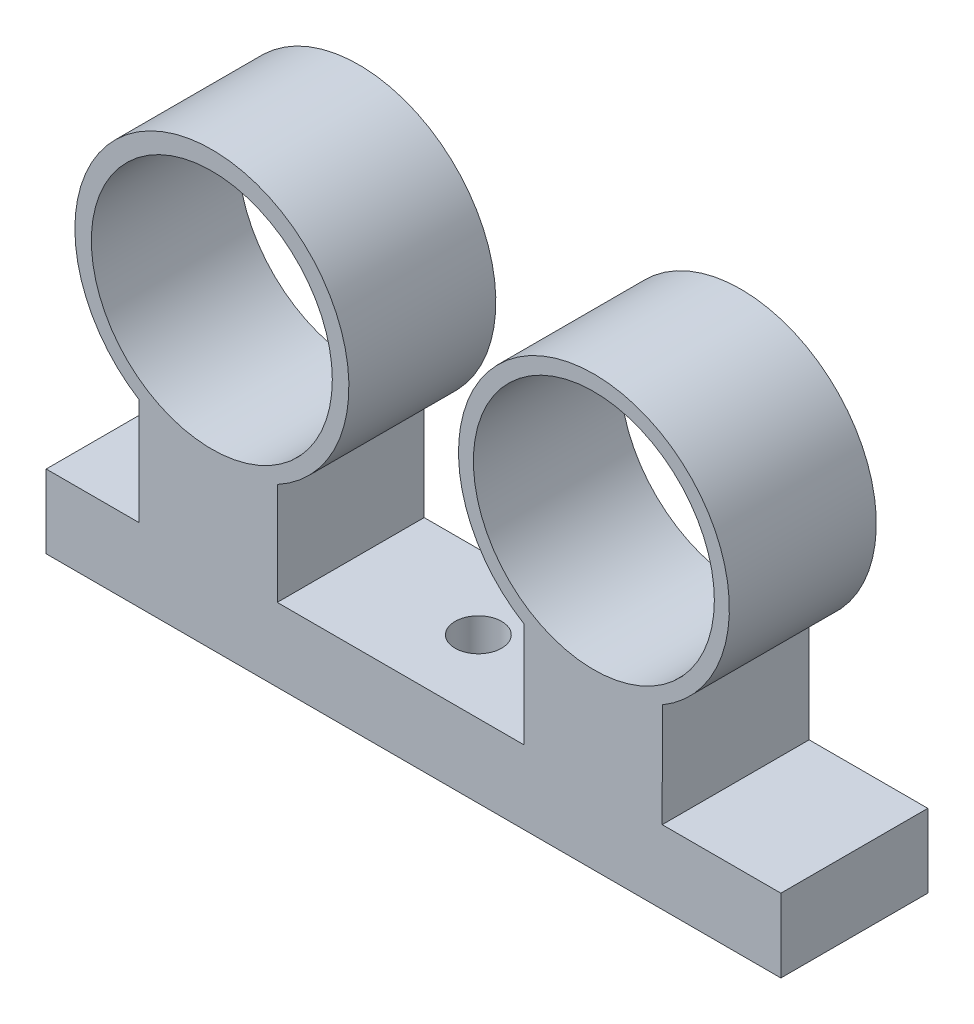
SolidWorks part; units mm, degrees
ref_plane "Alzado" through (0, 0, 0) normal (0, 0, 1) x (1, 0, 0)
ref_plane "Planta" through (0, 0, 0) normal (0, 1, 0) x (1, 0, 0)
ref_plane "Vista lateral" through (0, 0, 0) normal (1, 0, 0) x (0, 0, -1)
sketch "Sketch1" plane through (0, 0, 0) normal (0, 0, 1) x (1, 0, 0)
  line L0 (-4.1885, 12.6077) -> (-4.1885, 5.3678)
  line L1 (-10.5195, 0.3678) -> (39.4805, 0.3678)
  line L2 (-10.5195, 0.3678) -> (-10.5195, 5.3678)
  line L4 (39.4805, 0.3678) -> (39.4805, 5.3678)
  line L5 (-10.5195, 0.3678) -> (39.4805, 5.3678) construction
  line L6 (-10.5195, 5.3678) -> (39.4805, 0.3678) construction
  line L8 (5.2058, 5.3678) -> (5.2058, 12.317)
  line L9 (22.0109, 12.4897) -> (22.0055, 5.3678)
  line L11 (31.4055, 5.3678) -> (31.4109, 12.4339)
  line L12 (-10.5195, 5.3678) -> (-4.1885, 5.3678)
  line L13 (5.2058, 5.3678) -> (22.0055, 5.3678)
  line L14 (31.4055, 5.3678) -> (39.4805, 5.3678)
  circle A0 centre (26.7532, 20.3678) radius 8.2
  circle A1 centre (0.7532, 20.3678) radius 8.2
  arc A5 (-4.1885, 12.6077) -> (5.2058, 12.317) centre (0.7577, 20.5122) cw
  arc A6 (22.0109, 12.4897) -> (31.4109, 12.4339) centre (26.758, 20.391) cw
  point P4 (17.3377, 2.5)
  dimension "D3" = 16.4
  dimension "D5" = 16.4
  dimension "D4" = 9.4
  dimension "D1" = 5
  dimension "D2" = 50
  dimension "D6" = 26
extrude "Boss-Extrude1" add sketch "Sketch1" along normal blind 10
sketch "Sketch2" plane through (0, 5.3678, 0) normal (0, 1, 0) x (1, 0, 0)
  circle A0 centre (13.9586, -5.0671) radius 1.585
  dimension "D1" = 3.17
extrude "Cut-Extrude1" cut sketch "Sketch2" against normal blind 10
